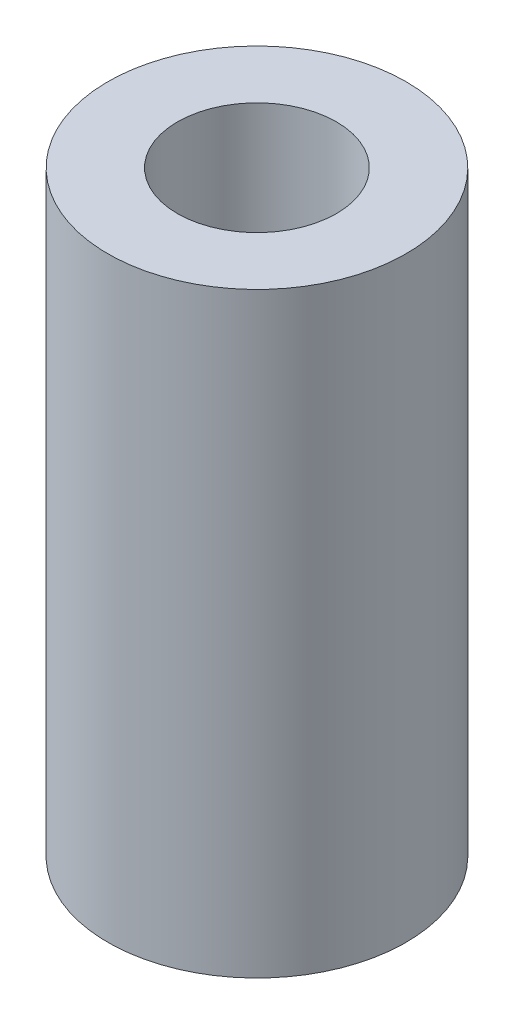
SolidWorks part; units mm, degrees
material "6063-T5"
ref_plane "Alzado" through (0, 0, 0) normal (0, 0, 1) x (1, 0, 0)
ref_plane "Planta" through (0, 0, 0) normal (0, 1, 0) x (1, 0, 0)
ref_plane "Vista lateral" through (0, 0, 0) normal (1, 0, 0) x (0, 0, -1)
ref_plane "Plano1" through (0, 0, 0) normal (0, -1, 0) x (1, 0, 0)
sketch "Croquis1" plane through (0, 0, 0) normal (0, -1, 0) x (1, 0, 0)
  circle A0 centre (0, 0) radius 1.6
  circle A1 centre (0, 0) radius 3
  dimension "D1" = 3.2
  dimension "D2" = 6
extrude "Saliente-Extruir1" add sketch "Croquis1" against normal blind 12
equation "\"L\"= 1"
